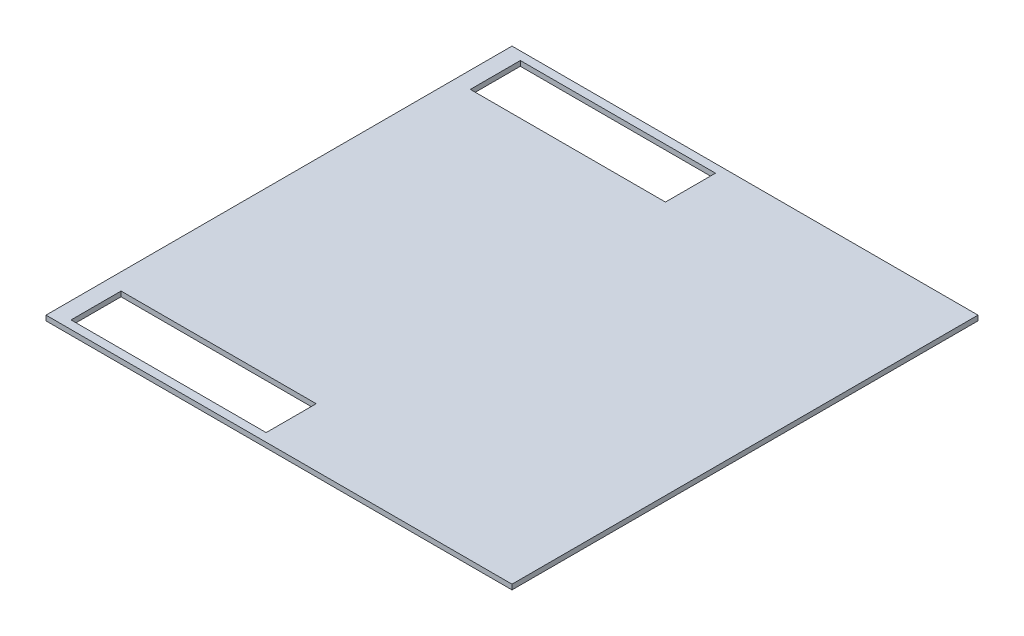
SolidWorks part; units mm, degrees
material "ENPH 253 Hardboard"
ref_plane "Front Plane" through (0, 0, 0) normal (0, 0, 1) x (1, 0, 0)
ref_plane "Top Plane" through (0, 0, 0) normal (0, 1, 0) x (1, 0, 0)
ref_plane "Right Plane" through (0, 0, 0) normal (1, 0, 0) x (0, 0, -1)
sketch "Sketch1" plane through (0, 0, 0) normal (0, 1, 0) x (1, 0, 0)
  line L0 (0, -139.7) -> (0, 139.7) construction
  line L1 (-139.7, 139.7) -> (139.7, 139.7)
  line L2 (-139.7, 139.7) -> (-139.7, -139.7)
  line L3 (-139.7, -139.7) -> (139.7, -139.7)
  line L4 (139.7, 139.7) -> (139.7, -139.7)
  line L5 (-139.7, 139.7) -> (139.7, -139.7) construction
  line L6 (-139.7, -139.7) -> (139.7, 139.7) construction
  line L7 (-129.7, 134.7) -> (-12.7, 134.7)
  line L8 (-129.7, 134.7) -> (-129.7, 104.7)
  line L9 (-129.7, 104.7) -> (-12.7, 104.7)
  line L10 (-12.7, 134.7) -> (-12.7, 104.7)
  line L12 (-139.7, 0) -> (139.7, 0) construction
  line L22 (-129.7, -104.7) -> (-12.7, -104.7)
  line L23 (-12.7, -134.7) -> (-12.7, -104.7)
  line L24 (-129.7, -134.7) -> (-12.7, -134.7)
  line L25 (-129.7, -134.7) -> (-129.7, -104.7)
  point P0 (0, 0)
  dimension "D1" = 279.4
  dimension "D2" = 279.4
  dimension "D3" = 5
  dimension "D4" = 30
  dimension "D5" = 117
  dimension "D6" = 10
extrude "Boss-Extrude1" add sketch "Sketch1" along normal blind 3
